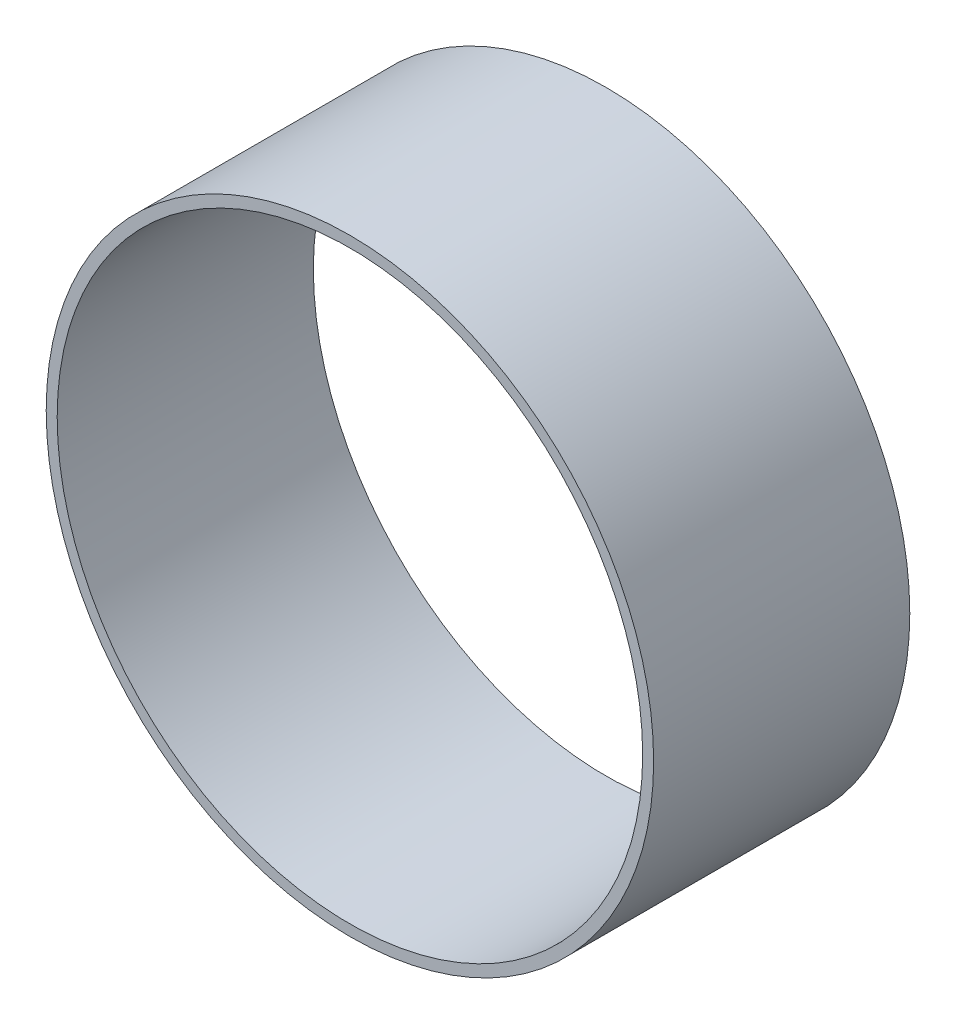
SolidWorks part; units mm, degrees
ref_plane "Спереди" through (0, 0, 0) normal (0, 0, 1) x (1, 0, 0)
ref_plane "Сверху" through (0, 0, 0) normal (0, 1, 0) x (1, 0, 0)
ref_plane "Справа" through (0, 0, 0) normal (1, 0, 0) x (0, 0, -1)
sketch "Эскиз1" plane through (0, 0, 0) normal (0, 0, 1) x (1, 0, 0)
  circle A0 centre (0, 0) radius 83
  circle A1 centre (0, 0) radius 80
extrude "Rotor_shell" add sketch "Эскиз1" along normal blind 70 from offset 35
